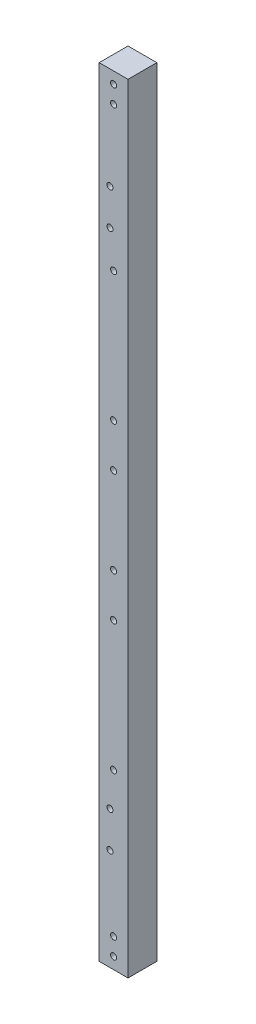
SolidWorks part; units mm, degrees
ref_plane "前视基准面" through (0, 0, 0) normal (0, 0, 1) x (1, 0, 0)
ref_plane "上视基准面" through (0, 0, 0) normal (0, 1, 0) x (1, 0, 0)
ref_plane "右视基准面" through (0, 0, 0) normal (1, 0, 0) x (0, 0, -1)
sketch "草图1" plane through (0, 0, 0) normal (0, 1, 0) x (1, 0, 0)
  line L1 (-43.8462, 73.4615) -> (-23.8462, 73.4615)
  line L2 (-43.8462, 73.4615) -> (-43.8462, 53.4615)
  line L3 (-43.8462, 53.4615) -> (-23.8462, 53.4615)
  line L4 (-23.8462, 73.4615) -> (-23.8462, 53.4615)
  dimension "D1" = 20
  dimension "D2" = 20
extrude "凸台-拉伸1" add sketch "草图1" along normal blind 540
sketch "草图2" plane through (0, 0, -53.4615) normal (0, 0, 1) x (1, 0, 0)
  line L0 (-43.8462, 270) -> (-43.8462, 330) construction
  line L1 (-43.8462, 540) -> (-43.8462, 0) construction
  line L2 (-33.8462, 0) -> (-33.8462, 640.9224) construction
  line L3 (-43.8462, 0) -> (-23.8462, 0) construction
  line L4 (-43.8462, 270) -> (24.2609, 270) construction
  circle A0 centre (-33.8462, 330) radius 2.1
  circle A1 centre (-33.8462, 210) radius 2.1
  circle A3 centre (-33.8462, 420) radius 2.1
  circle A4 centre (-33.8462, 300) radius 2.1
  circle A5 centre (-33.8462, 240) radius 2.1
  circle A6 centre (-33.8462, 120) radius 2.1
  dimension "D2" = 4.2
  dimension "D4" = 4.2
  dimension "D5" = 30
  dimension "D6" = 4.2
  dimension "D7" = 120
  dimension "D8" = 30
  dimension "D9" = 4.2
  dimension "D10" = 4.2
  dimension "D1" = 60
  dimension "D3" = 90
extrude "切除-拉伸1" cut sketch "草图2" against normal through all
sketch "草图3" plane through (0, 0, -53.4615) normal (0, 0, 1) x (1, 0, 0)
  line L0 (-36.3462, 0) -> (-36.3462, 70.5) construction
  line L1 (-43.8462, 0) -> (-23.8462, 0) construction
  line L2 (-36.3462, 70.5) -> (-36.3462, 95.5) construction
  line L3 (-43.8462, 270) -> (35.831, 270) construction
  line L4 (-43.8462, 540) -> (-43.8462, 0) construction
  line L5 (-36.3462, 95.5) -> (-36.3462, 552.7615) construction
  line L6 (-33.8462, 0) -> (-36.3462, 0) construction
  line L7 (-36.3462, 469.5) -> (-36.3462, 444.5) construction
  line L8 (-36.3462, 540) -> (-36.3462, 488.7) construction
  line L9 (-43.8462, 540) -> (-23.8462, 540) construction
  circle A4 centre (-36.3462, 70.5) radius 2.1
  circle A5 centre (-36.3462, 95.5) radius 2.1
  circle A12 centre (-36.3462, 444.5) radius 2.1
  circle A13 centre (-36.3462, 469.5) radius 2.1
  dimension "D3" = 4.2
  dimension "D4" = 4.2
  dimension "D1" = 70.5
  dimension "D2" = 25
  dimension "D5" = 7.5
extrude "切除-拉伸2" cut sketch "草图3" against normal through all
sketch "草图4" plane through (0, 0, -53.4615) normal (0, 0, 1) x (1, 0, 0)
  line L0 (-33.8462, 0) -> (-33.8462, 8) construction
  line L1 (-43.8462, 0) -> (-23.8462, 0) construction
  line L2 (-33.8462, 8) -> (-33.8462, 20) construction
  line L3 (-43.8462, 270) -> (1.8483, 270) construction
  line L4 (-43.8462, 540) -> (-43.8462, 0) construction
  line L5 (-33.8462, 532) -> (-33.8462, 520) construction
  circle A0 centre (-33.8462, 8) radius 2.1
  circle A1 centre (-33.8462, 20) radius 2.1
  circle A2 centre (-33.8462, 520) radius 2.1
  circle A3 centre (-33.8462, 532) radius 2.1
  dimension "D3" = 4.2
  dimension "D4" = 4.2
  dimension "D1" = 8
  dimension "D2" = 12
extrude "切除-拉伸3" cut sketch "草图4" against normal blind 140
